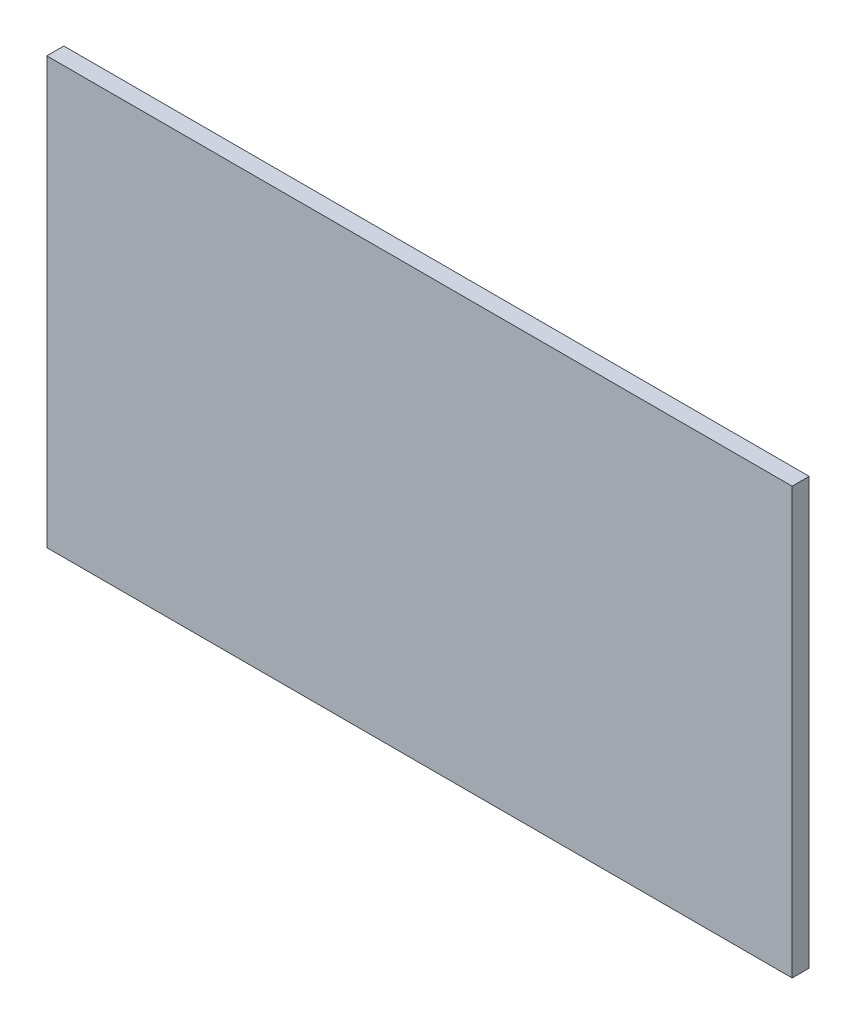
SolidWorks part; units mm, degrees
ref_plane "前视基准面" through (0, 0, 0) normal (0, 0, 1) x (1, 0, 0)
ref_plane "上视基准面" through (0, 0, 0) normal (0, 1, 0) x (1, 0, 0)
ref_plane "右视基准面" through (0, 0, 0) normal (1, 0, 0) x (0, 0, -1)
other "Configuration Table"
sketch "草图1" plane through (0, 0, 0) normal (0, 0, 1) x (1, 0, 0)
  line L1 (-35, 38) -> (35, 38)
  line L2 (-35, 38) -> (-35, 78)
  line L3 (-35, 78) -> (35, 78)
  line L4 (35, 38) -> (35, 78)
extrude "70x40_camera_board_vertical" add sketch "草图1" along normal blind 1.6 from offset 0
